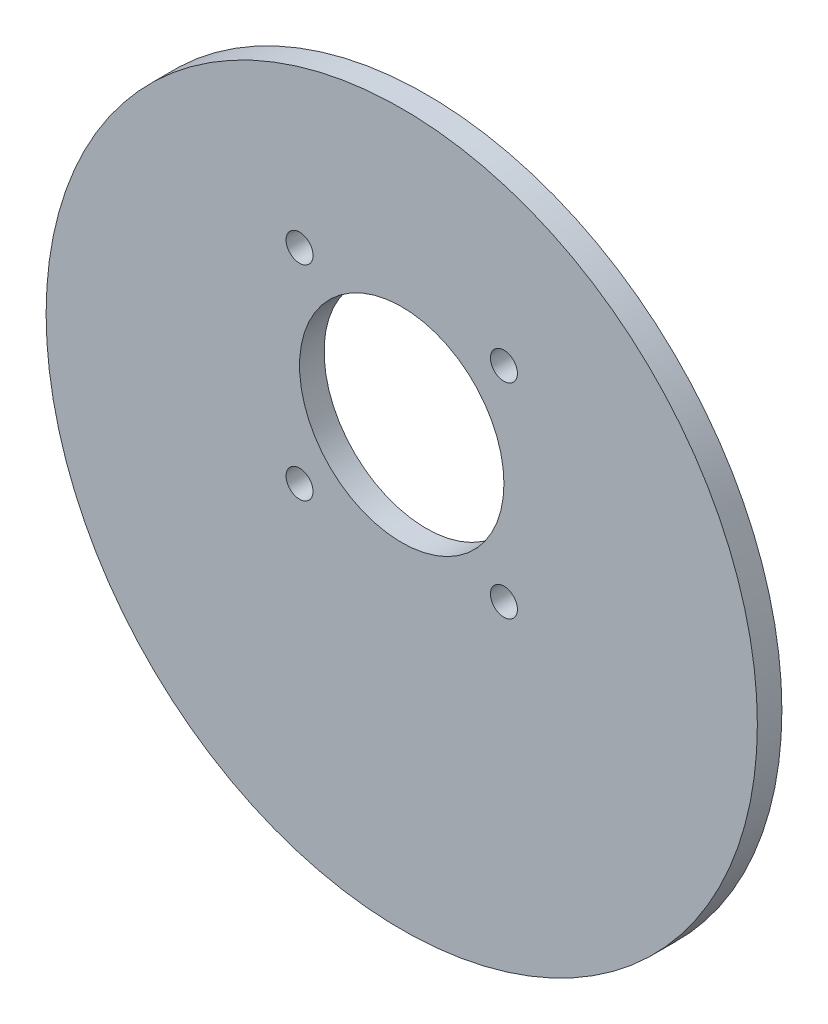
SolidWorks part; units mm, degrees
ref_plane "Front Plane" through (0, 0, 0) normal (0, 0, 1) x (1, 0, 0)
ref_plane "Top Plane" through (0, 0, 0) normal (0, 1, 0) x (1, 0, 0)
ref_plane "Right Plane" through (0, 0, 0) normal (1, 0, 0) x (0, 0, -1)
sketch "Sketch1" plane through (0, 0, 0) normal (0, 0, 1) x (1, 0, 0)
  circle A0 centre (0, 0) radius 43.5 construction
  circle A1 centre (0, 0) radius 43.5
  circle A2 centre (12.5, 22.5) radius 2.15 construction
  circle A3 centre (-12.5, 22.5) radius 2.15 construction
  circle A4 centre (12.5, -2.5) radius 2.15 construction
  circle A5 centre (-12.5, -2.5) radius 2.15 construction
  circle A6 centre (12.5, 22.5) radius 2.15 construction
  circle A7 centre (-12.5, 22.5) radius 2.15 construction
  circle A8 centre (12.5, -2.5) radius 2.15 construction
  circle A9 centre (-12.5, -2.5) radius 2.15 construction
  circle A10 centre (-12.5, -2.5) radius 1.65
  circle A11 centre (12.5, -2.5) radius 1.65
  circle A12 centre (12.5, 22.5) radius 1.65
  circle A13 centre (-12.5, 22.5) radius 1.65
  circle A14 centre (0, 10) radius 12.5 construction
  circle A15 centre (0, 10) radius 12.5
  dimension "D1" = 3.3
extrude "Boss-Extrude1" add sketch "Sketch1" along normal blind 3
